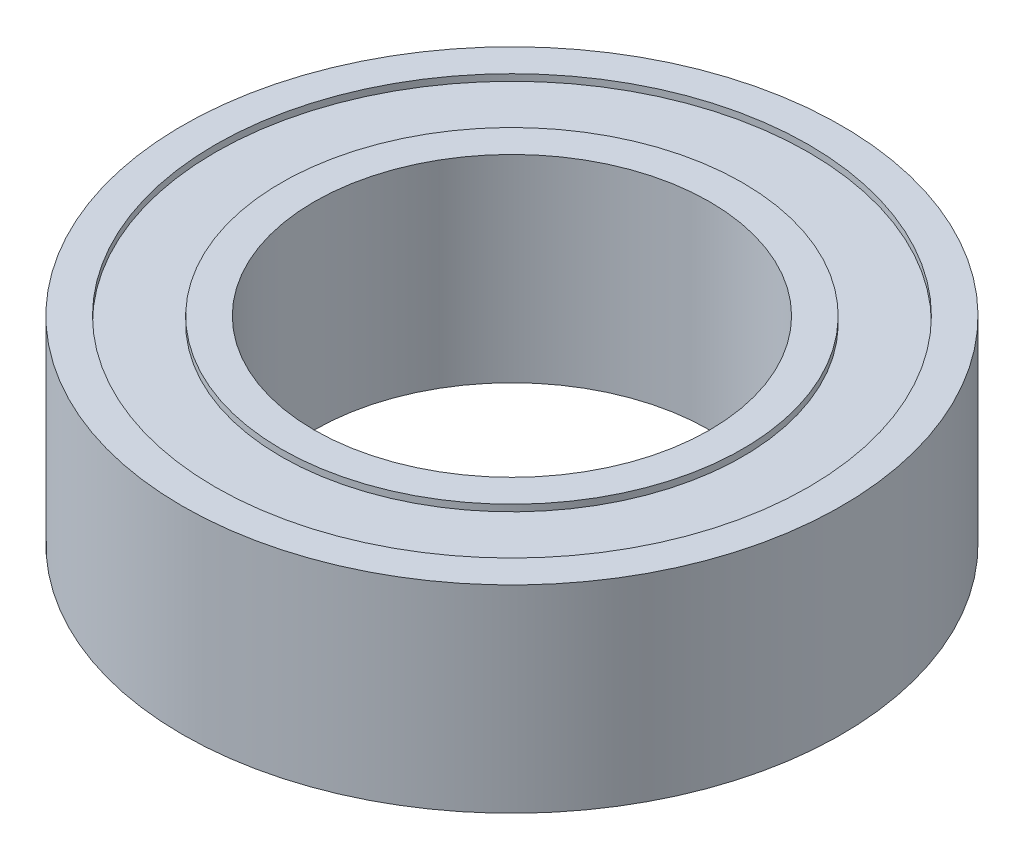
SolidWorks part; units mm, degrees
ref_plane "前视基准面" through (0, 0, 0) normal (0, 0, 1) x (1, 0, 0)
ref_plane "上视基准面" through (0, 0, 0) normal (0, 1, 0) x (1, 0, 0)
ref_plane "右视基准面" through (0, 0, 0) normal (1, 0, 0) x (0, 0, -1)
other "Configuration Table"
sketch "草图1" plane through (0, 0, 0) normal (0, 1, 0) x (1, 0, 0)
  circle A0 centre (0, 0) radius 5
  dimension "D1" = 10
extrude "凸台-拉伸1" add sketch "草图1" along normal blind 3
sketch "草图2" plane through (0, 3, 0) normal (0, 1, 0) x (1, 0, 0)
  circle A0 centre (0, 0) radius 3
  dimension "D1" = 6
extrude "切除-拉伸1" cut sketch "草图2" against normal up to next
sketch "草图3" plane through (0, 3, 0) normal (0, 1, 0) x (1, 0, 0)
  circle A0 centre (0, 0) radius 3.5
  circle A1 centre (0, 0) radius 4.5
  dimension "D1" = 9
  dimension "D2" = 7
extrude "切除-拉伸2" cut sketch "草图3" against normal blind 0.1
sketch "草图4" plane through (0, 0, 0) normal (0, -1, 0) x (1, 0, 0)
  circle A0 centre (0, 0) radius 4.5
  circle A1 centre (0, 0) radius 3.5
  dimension "D1" = 9
  dimension "D2" = 7
extrude "切除-拉伸3" cut sketch "草图4" against normal blind 0.1
